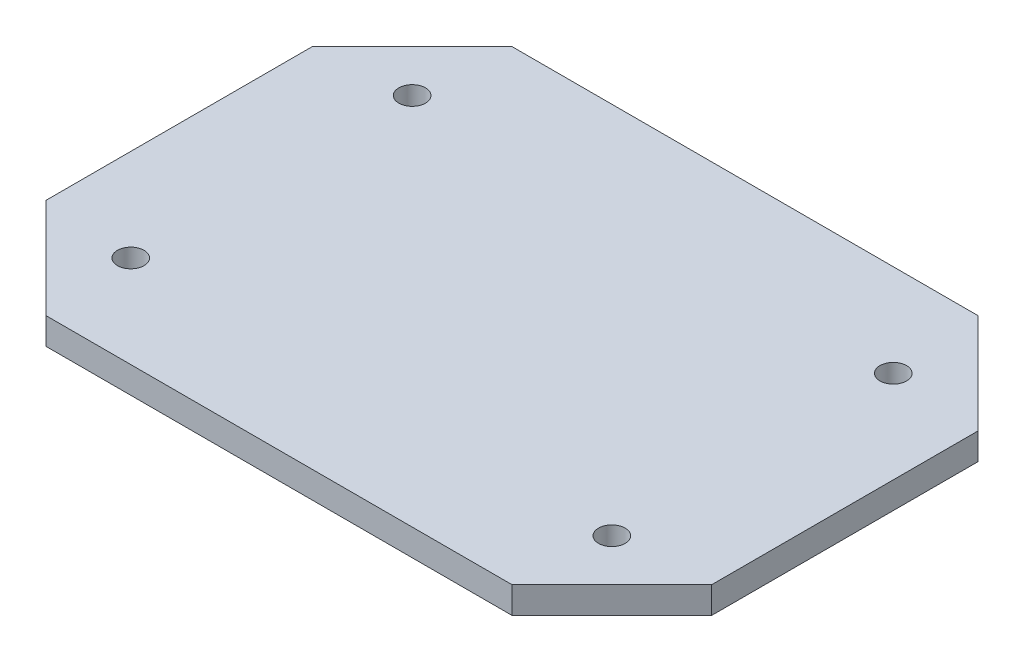
SolidWorks part; units mm, degrees
ref_plane "Front Plane" through (0, 0, 0) normal (0, 0, 1) x (1, 0, 0)
ref_plane "Top Plane" through (0, 0, 0) normal (0, 1, 0) x (1, 0, 0)
ref_plane "Right Plane" through (0, 0, 0) normal (1, 0, 0) x (0, 0, -1)
sketch "Sketch1" plane through (0, 0, 0) normal (0, 1, 0) x (1, 0, 0)
  line L0 (107.95, 88.9) -> (19.05, 88.9)
  line L1 (0, 0) -> (127, 0) construction
  line L2 (0, 0) -> (0, 88.9) construction
  line L3 (0, 88.9) -> (127, 88.9) construction
  line L4 (127, 0) -> (127, 88.9) construction
  line L5 (19.05, 88.9) -> (0, 69.85)
  line L6 (0, 69.85) -> (0, 19.05)
  line L7 (63.5, 88.9) -> (63.5, 0) construction
  line L8 (107.95, 88.9) -> (127, 69.85)
  line L9 (127, 69.85) -> (127, 19.05)
  line L10 (127, 44.45) -> (0, 44.45) construction
  line L11 (107.95, 0) -> (127, 19.05)
  line L12 (107.95, 0) -> (19.05, 0)
  line L13 (19.05, 0) -> (0, 19.05)
  line L14 (17.6072, 71.2928) -> (9.525, 79.375) construction
  circle A0 centre (17.6072, 71.2928) radius 2.54
  circle A1 centre (17.6072, 17.6072) radius 2.54
  circle A2 centre (109.3928, 17.6072) radius 2.54
  circle A3 centre (109.3928, 71.2928) radius 2.54
  point P22 (0, 0)
  point P23 (0, 0)
  point P24 (0, 0)
  point P25 (1.8391, 67.5786)
  dimension "D5" = 5.08
  dimension "D1" = 127
  dimension "D2" = 88.9
  dimension "D3" = 45
  dimension "D4" = 19.05
  dimension "D6" = 11.43
extrude "Boss-Extrude1" add sketch "Sketch1" along normal blind 5.08
